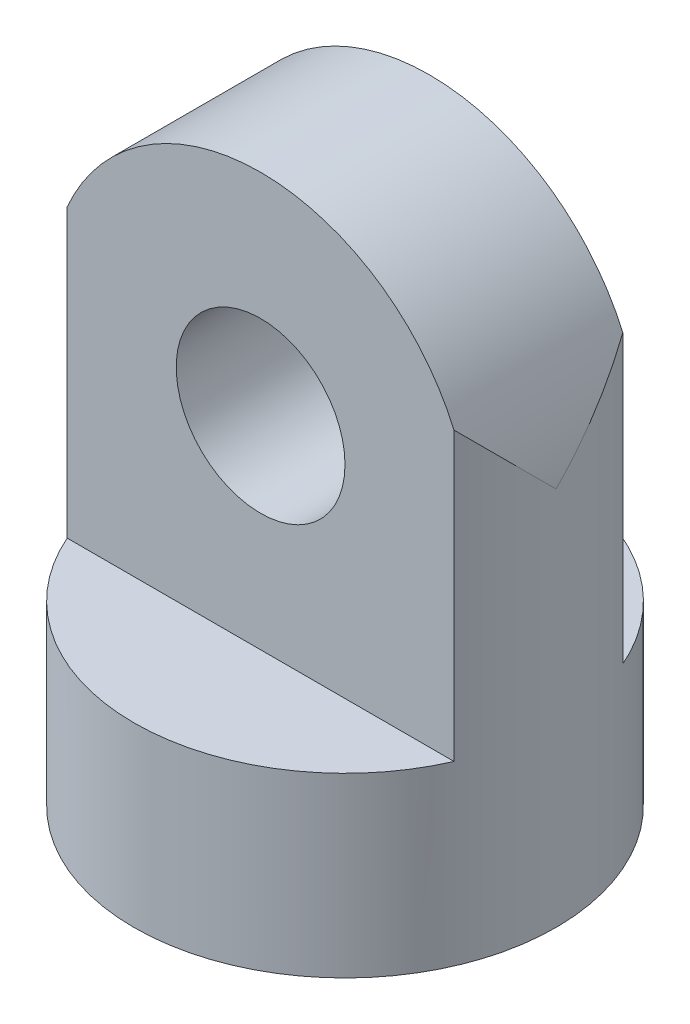
SolidWorks part; units mm, degrees
ref_plane "Front Plane" through (0, 0, 0) normal (0, 0, 1) x (1, 0, 0)
ref_plane "Top Plane" through (0, 0, 0) normal (0, 1, 0) x (1, 0, 0)
ref_plane "Right Plane" through (0, 0, 0) normal (1, 0, 0) x (0, 0, -1)
sketch "Sketch1" plane through (0, 0, 0) normal (0, 1, 0) x (1, 0, 0)
  circle A0 centre (0, 0) radius 1
  circle A1 centre (0, 0) radius 2.5
  dimension "D1" = 2
  dimension "D2" = 5
extrude "Boss-Extrude2" add sketch "Sketch1" along normal blind 2.1
sketch "Sketch2" plane through (0, 0, 0) normal (0, 0, 1) x (1, 0, 0)
  line L0 (2.5, 4.5) -> (2.5, 0)
  line L2 (2.5, 0) -> (-2.5, 0)
  line L3 (-2.5, 0) -> (-2.5, 4.5)
  arc A2 (2.5, 4.5) -> (-2.5, 4.5) centre (0, 4.5) ccw
  circle A3 centre (0, 4.5) radius 1
  dimension "D2" = 5
  dimension "D3" = 4.5
  dimension "D1" = 2
  dimension "D4" = 4.5
extrude "Boss-Extrude3" add sketch "Sketch2" along normal mid plane 2
sketch "Sketch4" plane through (0, 0, 0) normal (0, -1, 0) x (1, 0, 0)
  circle A0 centre (0, 0) radius 1
  dimension "D1" = 2
extrude "Cut-Extrude13" cut sketch "Sketch4" against normal blind 2
sketch "Sketch6" plane through (0, 0, 0) normal (0, -1, 0) x (1, 0, 0)
  circle A0 centre (0, 0) radius 2.5
extrude "Cut-Extrude14" cut sketch "Sketch6" against normal through all flip side to cut
